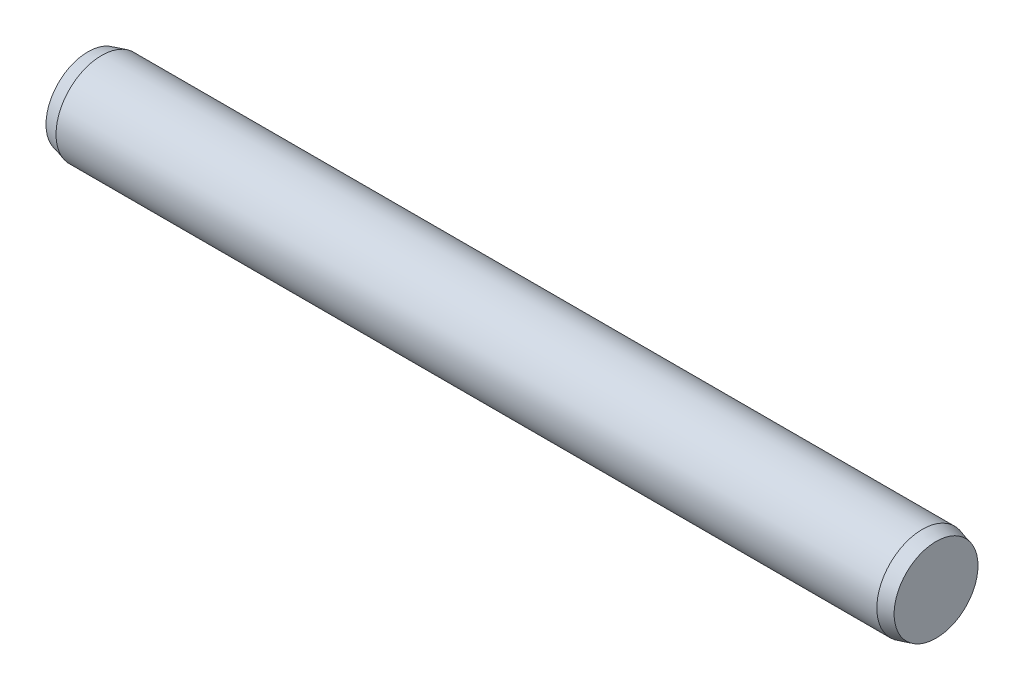
SolidWorks part; units mm, degrees
ref_plane "Front Plane" through (0, 0, 0) normal (0, 0, 1) x (1, 0, 0)
ref_plane "Top Plane" through (0, 0, 0) normal (0, 1, 0) x (1, 0, 0)
ref_plane "Right Plane" through (0, 0, 0) normal (1, 0, 0) x (0, 0, -1)
sketch "Sketch1" plane through (0, 0, 0) normal (0, 0, 1) x (1, 0, 0)
  line L0 (-9, 0) -> (9, 0) construction
  line L1 (9, 1) -> (9, -1) construction
  line L2 (-9, 1) -> (-9, -1) construction
  line L3 (9.3, 1) -> (9.3, -1) construction
  line L4 (-9.3, 1) -> (-9.3, -1) construction
  line L5 (-9, 0) -> (-9.3, 0) construction
  line L6 (9, 0) -> (9.3, 0) construction
  dimension "Dia" = 2
  dimension "Length" = 18
  dimension "C" = 0.3
  dimension "D1" = 0.3
sketch "Sketch2" plane through (0, 0, 0) normal (1, 0, 0) x (0, 0, -1)
  circle A0 centre (0, 0) radius 1
extrude "Extrude1" add sketch "Sketch2" against normal up to vertex (9 mm away) and the other way up to vertex (9 mm away) up to point (-9, 1, 0) other way up to point (9, 1, 0)
sketch "Sketch3" plane through (9, 0, 0) normal (1, 0, 0) x (0, 0, -1)
  circle A1 centre (0, 0) radius 1
  circle A2 centre (0, 0) radius 1
  dimension "D1" = 0
extrude "Extrude2" add sketch "Sketch3" along normal up to vertex (0.3 mm away) draft 15 up to point (9.3, 0, 0)
sketch "Sketch4" plane through (-9, 0, 0) normal (-1, 0, 0) x (0, 0, 1)
  circle A1 centre (0, 0) radius 1
  circle A2 centre (0, 0) radius 1
  dimension "D1" = 0
extrude "Extrude3" add sketch "Sketch4" along normal up to vertex (0.3 mm away) draft 15 up to point (-9.3, 0, 0)
equation "\"D1@Sketch1\" = \"C@Sketch1\""
